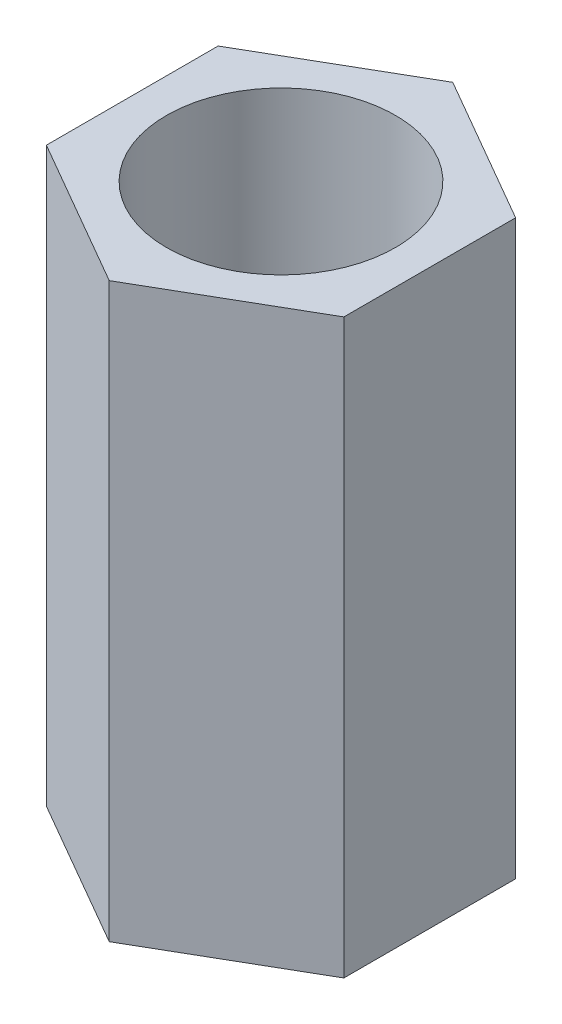
SolidWorks part; units mm, degrees
material "黄铜"
ref_plane "前视基准面" through (0, 0, 0) normal (0, 0, 1) x (1, 0, 0)
ref_plane "上视基准面" through (0, 0, 0) normal (0, 1, 0) x (1, 0, 0)
ref_plane "右视基准面" through (0, 0, 0) normal (1, 0, 0) x (0, 0, -1)
other "Configuration Table"
sketch "草图1" plane through (0, 0, 0) normal (0, 1, 0) x (1, 0, 0)
  line L1 (0, 3) -> (-2.5981, 1.5)
  line L2 (-2.5981, 1.5) -> (-2.5981, -1.5)
  line L3 (-2.5981, -1.5) -> (0, -3)
  line L4 (0, -3) -> (2.5981, -1.5)
  line L5 (2.5981, -1.5) -> (2.5981, 1.5)
  line L6 (2.5981, 1.5) -> (0, 3)
  circle A0 centre (0, 0) radius 2
  circle A1 centre (0, 0) radius 2.5981 construction
  dimension "D1" = 4
  dimension "D2" = 6
extrude "凸台-拉伸1" add sketch "草图1" along normal blind 10
